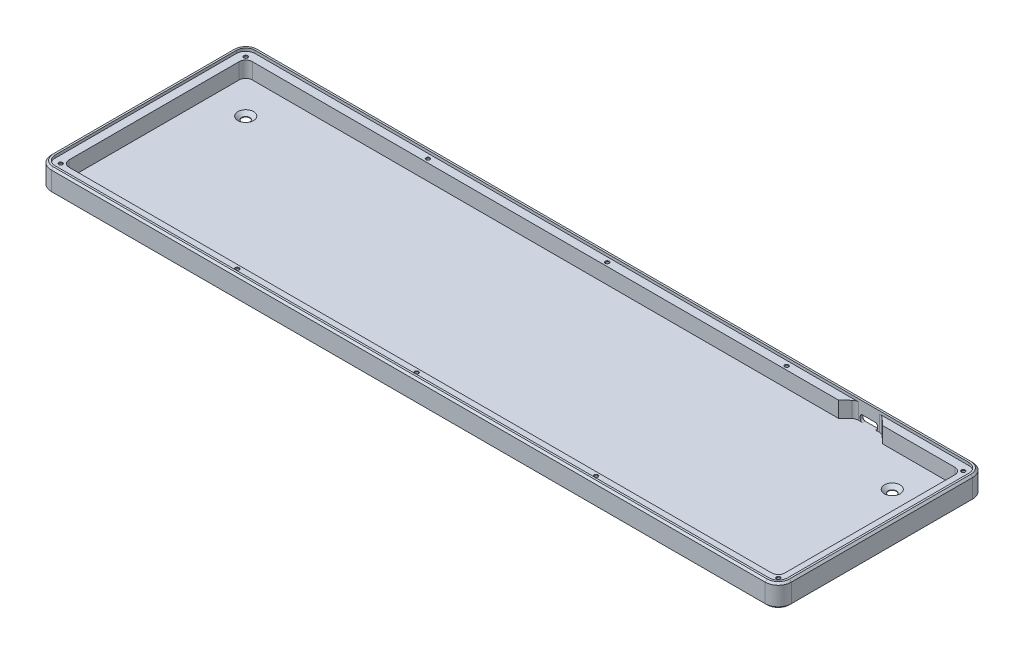
SolidWorks part; units mm, degrees
material "6061-T6 (SS)"
ref_plane "Front" through (0, 0, 0) normal (0, 0, 1) x (1, 0, 0)
ref_plane "Top" through (0, 0, 0) normal (0, 1, 0) x (1, 0, 0)
ref_plane "Right" through (0, 0, 0) normal (1, 0, 0) x (0, 0, -1)
sketch "Sketch1" plane through (0, 0, 0) normal (0, 1, 0) x (1, 0, 0)
  line L0 (-5, 109) -> (-387, 109)
  line L1 (-5, 0) -> (-387, 0) construction
  line L2 (0, 5) -> (0, 102) construction
  line L3 (-5, 107) -> (-387, 107) construction
  line L4 (-392, 5) -> (-392, 102) construction
  line L5 (-394, 5) -> (-394, 102)
  line L6 (-5, -2) -> (-387, -2)
  line L7 (2, 5) -> (2, 102)
  arc A0 (0, 102) -> (-5, 107) centre (-5, 102) ccw construction
  arc A1 (-5, 0) -> (0, 5) centre (-5, 5) ccw construction
  arc A2 (-387, 0) -> (-392, 5) centre (-387, 5) cw construction
  arc A3 (-387, 107) -> (-392, 102) centre (-387, 102) ccw construction
  arc A4 (-387, 109) -> (-394, 102) centre (-387, 102) ccw
  arc A5 (-387, -2) -> (-394, 5) centre (-387, 5) cw
  arc A6 (-5, -2) -> (2, 5) centre (-5, 5) ccw
  arc A7 (2, 102) -> (-5, 109) centre (-5, 102) ccw
  point P9 (0, 0)
  dimension "D3" = 5
  dimension "D1" = 107
  dimension "D2" = 392
  dimension "D4" = 2
extrude "Boss-Extrude1" add sketch "Sketch1" along normal blind 12
sketch "Sketch2" plane through (0, 12, 0) normal (0, 1, 0) x (1, 0, 0)
  line L0 (0, 5) -> (0, 102) construction
  line L1 (-5, 0) -> (-387, 0) construction
  line L2 (-392, 5) -> (-392, 102) construction
  line L3 (-5, 107) -> (-387, 107) construction
  line L4 (0, 5) -> (0, 102)
  line L5 (-5, 0) -> (-387, 0)
  line L6 (-392, 5) -> (-392, 102)
  line L7 (-5, 107) -> (-387, 107)
  arc A0 (0, 102) -> (-5, 107) centre (-5, 102) ccw construction
  arc A1 (-5, 0) -> (0, 5) centre (-5, 5) ccw construction
  arc A2 (-392, 5) -> (-387, 0) centre (-387, 5) ccw construction
  arc A3 (-387, 107) -> (-392, 102) centre (-387, 102) ccw construction
  arc A4 (0, 102) -> (-5, 107) centre (-5, 102) ccw
  arc A5 (-5, 0) -> (0, 5) centre (-5, 5) ccw
  arc A6 (-392, 5) -> (-387, 0) centre (-387, 5) ccw
  arc A7 (-387, 107) -> (-392, 102) centre (-387, 102) ccw
extrude "Cut-Extrude1" cut sketch "Sketch2" against normal blind 1.5
sketch "Sketch3" plane through (0, 10.5, 0) normal (0, 1, 0) x (1, 0, 0)
  line L8 (2, 5) -> (2, 102) construction
  line L9 (-384, 102.5) -> (-8, 102.5)
  line L10 (-387.5, 99) -> (-387.5, 8)
  line L11 (-384, 4.5) -> (-8, 4.5)
  line L12 (-4.5, 99) -> (-4.5, 8)
  line L13 (-394, 102) -> (-394, 5) construction
  line L14 (-5, 109) -> (-387, 109) construction
  line L15 (-387, -2) -> (-5, -2) construction
  arc A6 (-8, 102.5) -> (-4.5, 99) centre (-8, 99) cw
  arc A7 (-8, 4.5) -> (-4.5, 8) centre (-8, 8) ccw
  arc A8 (-387.5, 8) -> (-384, 4.5) centre (-384, 8) ccw
  arc A9 (-384, 102.5) -> (-387.5, 99) centre (-384, 99) ccw
  dimension "D5" = 3.5
  dimension "D1" = 6.5
  dimension "D2" = 6.5
  dimension "D3" = 6.5
  dimension "D4" = 6.5
extrude "Cut-Extrude2" cut sketch "Sketch3" against normal blind 8.5
sketch "Sketch4" plane through (0, 10.5, 0) normal (0, 1, 0) x (1, 0, 0)
  line L0 (-5, 107) -> (-387, 107) construction
  line L1 (-392, 102) -> (-392, 5) construction
  line L2 (-387, 0) -> (-5, 0) construction
  line L4 (0, 5) -> (0, 102) construction
  circle A0 centre (-388, 103) radius 1.1 construction
  circle A1 centre (-4, 103) radius 1.1 construction
  circle A2 centre (-4, 4) radius 1.1 construction
  circle A3 centre (-388, 4) radius 1.1 construction
  circle A4 centre (-292, 104.5) radius 1.1 construction
  circle A5 centre (-196, 104.5) radius 1.1 construction
  circle A6 centre (-100, 104.5) radius 1.1 construction
  circle A7 centre (-292, 2.5) radius 1.1 construction
  circle A8 centre (-196, 2.5) radius 1.1 construction
  circle A9 centre (-100, 2.5) radius 1.1 construction
  dimension "D3" = 2.2
  dimension "D1" = 4
  dimension "D2" = 4
  dimension "D4" = 2.5
  dimension "D5" = 2.5
  dimension "D6" = 4
  dimension "D7" = 4
  dimension "D8" = 96
  dimension "D9" = 96
  dimension "D10" = 96
hole_wizard "M2x0.4 Tapped Hole1" positions "3DSketch3" profile "Sketch12" tap size "M2x0.4" standard "ANSI Metric"
sketch3d "3DSketch3"
  point P0 (-388, 10.5, -103)
  point P4 (-292, 10.5, -104.5)
  point P7 (-196, 10.5, -104.5)
  point P10 (-100, 10.5, -104.5)
  point P13 (-4, 10.5, -103)
  point P16 (-4, 10.5, -4)
  point P19 (-100, 10.5, -2.5)
  point P22 (-196, 10.5, -2.5)
  point P25 (-292, 10.5, -2.5)
  point P28 (-388, 10.5, -4)
sketch "Sketch12" plane through (-388, 10.5, -103) normal (1, 0, 0) x (0, 0, 1)
  line L0 (0, 0) -> (0, 6.4807)
  line L1 (0, 6.4807) -> (0.8, 6)
  line L2 (0.8, 6) -> (0.8, 0.225)
  line L3 (0.8, 0.225) -> (1.025, 0)
  line L5 (1.025, 0) -> (0, 0)
  line L6 (-0.8, 0.225) -> (-1.025, 0) construction
  line L10 (0, 6.4807) -> (-0.8, 6) construction
  line L11 (0, -6.35) -> (0, 107.95) construction
  dimension "Tap Drill Dia." = 1.6
  dimension "Tap Drill Depth" = 6
  dimension "Near C'Sink Dia." = 2.05
  dimension "Near C'Sink Angle" = 90
  dimension "Drill Angle" = 118
cosmetic thread "Hole Thread2" parameters "D1"=6, "D2"=2
cosmetic thread "Hole Thread3" parameters "D1"=6, "D2"=2
cosmetic thread "Hole Thread4" parameters "D1"=6, "D2"=2
cosmetic thread "Hole Thread5" parameters "D1"=6, "D2"=2
cosmetic thread "Hole Thread6" parameters "D1"=6, "D2"=2
cosmetic thread "Hole Thread7" parameters "D1"=6, "D2"=2
cosmetic thread "Hole Thread8" parameters "D1"=6, "D2"=2
cosmetic thread "Hole Thread9" parameters "D1"=6, "D2"=2
cosmetic thread "Hole Thread10" parameters "D1"=6, "D2"=2
cosmetic thread "Hole Thread11" parameters "D1"=6, "D2"=2
sketch "Sketch13" plane through (0, 2, 0) normal (0, 1, 0) x (1, 0, 0)
  line L0 (-5, 109) -> (-387, 109) construction
  line L1 (-394, 102) -> (-394, 5) construction
  line L2 (2, 5) -> (2, 102) construction
  circle A0 centre (-369, 84) radius 2 construction
  circle A1 centre (-23, 84) radius 2 construction
  dimension "D4" = 4
  dimension "D1" = 25
  dimension "D2" = 25
  dimension "D3" = 25
hole_wizard "CSK for M4 Flat Head Machine Screw2" positions "3DSketch8" profile "Sketch19" countersink size "M4" standard "ANSI Metric" end condition through all
sketch3d "3DSketch8"
  point P0 (-369, 2, -84)
  point P3 (-23, 2, -84)
sketch "Sketch19" plane through (-369, 2, -84) normal (1, 0, 0) x (0, 0, 1)
  line L0 (0, 0) -> (0, 2)
  line L1 (0, 2) -> (2.15, 2)
  line L2 (2.15, 2) -> (2.15, 1.7097)
  line L3 (2.15, 1.7097) -> (4.1875, 0)
  line L5 (4.1875, 0) -> (0, 0)
  line L6 (-2.15, 1.7097) -> (-4.1875, 0) construction
  line L11 (0, -6.35) -> (0, 107.95) construction
  dimension "Thru Hole Dia." = 4.3
  dimension "Thru Hole Depth" = 2
  dimension "Near C'Sink Dia." = 8.375
  dimension "Near C'Sink Angle" = 100
chamfer "Chamfer1" distance 1 angle 45 16 edges at (-0.0503, 0, -106.9497) (-196, 0, -109) (2, 0, -53.5) (-391.9497, 0, -106.9497) (-0.0503, 0, -0.0503) (-394, 0, -53.5) (-196, 0, 2) (-391.9497, 0, -0.0503) (2, 12, -53.5) (-0.0503, 12, -106.9497) (-0.0503, 12, -0.0503) (-196, 12, -109) (-196, 12, 2) (-391.9497, 12, -106.9497) (-391.9497, 12, -0.0503) (-394, 12, -53.5)
sketch "Sketch20" plane through (0, 2, 0) normal (0, 1, 0) x (1, 0, 0)
  line L0 (-5.5, 99.5) -> (-5.5, 79.8743) construction
  line L1 (-4.5, 8) -> (-4.5, 99) construction
  line L2 (-7.5, 101.5) -> (-41.2261, 101.5) construction
  line L3 (-8, 102.5) -> (-384, 102.5) construction
  line L4 (-45.6072, 101.5) -> (-50.4915, 106.0587)
  line L5 (-52.8796, 107) -> (-64.1204, 107)
  line L6 (-66.5085, 106.0587) -> (-71.3928, 101.5)
  line L7 (-71.3928, 101.5) -> (-45.6072, 101.5)
  arc A0 (-5.5, 99.5) -> (-7.5, 101.5) centre (-7.5, 99.5) ccw construction
  arc A1 (-52.8796, 107) -> (-50.4915, 106.0587) centre (-52.8796, 103.5) cw
  arc A2 (-66.5085, 106.0587) -> (-64.1204, 107) centre (-64.1204, 103.5) cw
  point P12 (-51.5, 107)
  point P18 (-65.5, 107)
  dimension "D3" = 2
  dimension "D9" = 3.5
  dimension "D1" = 1
  dimension "D2" = 1
  dimension "D4" = 5.5
  dimension "D5" = 5.8928
  dimension "D6" = 5.8928
  dimension "D7" = 40.1072
  dimension "D8" = 14
extrude "Cut-Extrude3" cut sketch "Sketch20" along normal blind 10
sketch "Sketch21" plane through (0, 0, -109) normal (0, 0, -1) x (-1, 0, 0)
  line L1 (55.1, 5.5) -> (61.9, 5.5)
  line L2 (53.85, 4.25) -> (53.85, 3.25)
  line L3 (55.1, 2) -> (61.9, 2)
  line L4 (63.15, 4.25) -> (63.15, 3.25)
  line L5 (64.1204, 10.5) -> (64.1204, 2) construction
  line L7 (52.8796, 2) -> (64.1204, 2) construction
  arc A0 (61.9, 2) -> (63.15, 3.25) centre (61.9, 3.25) ccw
  arc A1 (53.85, 3.25) -> (55.1, 2) centre (55.1, 3.25) ccw
  arc A2 (55.1, 5.5) -> (53.85, 4.25) centre (55.1, 4.25) ccw
  arc A3 (61.9, 5.5) -> (63.15, 4.25) centre (61.9, 4.25) cw
  point P10 (53.85, 5.5)
  point P13 (63.15, 5.5)
  point P14 (58.5, 5.5)
  dimension "D3" = 1.25
  dimension "D1" = 9.3
  dimension "D2" = 3.5
  dimension "D4" = 5.6204
  dimension "D5" = 0
extrude "Cut-Extrude4" cut sketch "Sketch21" against normal blind 10
sketch "Sketch22" plane through (0, 0, -109) normal (0, 0, -1) x (-1, 0, 0)
  line L0 (51.5, -6.125) -> (51.5, 4.7)
  line L1 (54.675, 7.875) -> (62.325, 7.875)
  line L2 (65.5, 4.7) -> (65.5, -6.125)
  line L3 (65.5, -6.125) -> (51.5, -6.125)
  line L4 (61.9, 5.5) -> (55.1, 5.5) construction
  arc A0 (62.325, 7.875) -> (65.5, 4.7) centre (62.325, 4.7) cw
  arc A1 (51.5, 4.7) -> (54.675, 7.875) centre (54.675, 4.7) cw
  point P6 (58.5, 5.5)
  dimension "D4" = 3.175
  dimension "D1" = 14
  dimension "D2" = 7
  dimension "D3" = 2.375
  dimension "D5" = 14
extrude "Cut-Extrude5" cut sketch "Sketch22" against normal blind 0.375
chamfer "Chamfer3" distance 0.254 angle 45 8 edges at (-58.5, 2, -108.625) (-62.7839, 2.3661, -108.625) (-54.2161, 2.3661, -108.625) (-63.15, 3.75, -108.625) (-53.85, 3.75, -108.625) (-62.7839, 5.1339, -108.625) (-54.2161, 5.1339, -108.625) (-58.5, 5.5, -108.625)
sketch "Sketch23" plane through (0, 10.5, 0) normal (0, 1, 0) x (1, 0, 0)
  line L6 (-4.5, 8) -> (-4.5, 99) construction
  line L7 (-22.5, 102) -> (-8.5, 102)
  line L8 (-22.5, 102) -> (-22.5, 103.5)
  line L9 (-19, 107) -> (-12, 107)
  line L10 (-8.5, 102) -> (-8.5, 103.5)
  line L13 (-5, 107) -> (-387, 107) construction
  arc A2 (-12, 107) -> (-8.5, 103.5) centre (-12, 103.5) cw
  arc A3 (-22.5, 103.5) -> (-19, 107) centre (-19, 103.5) cw
  dimension "D5" = 3.5
  dimension "D6" = 14
  dimension "D7" = 5
  dimension "D8" = 4
